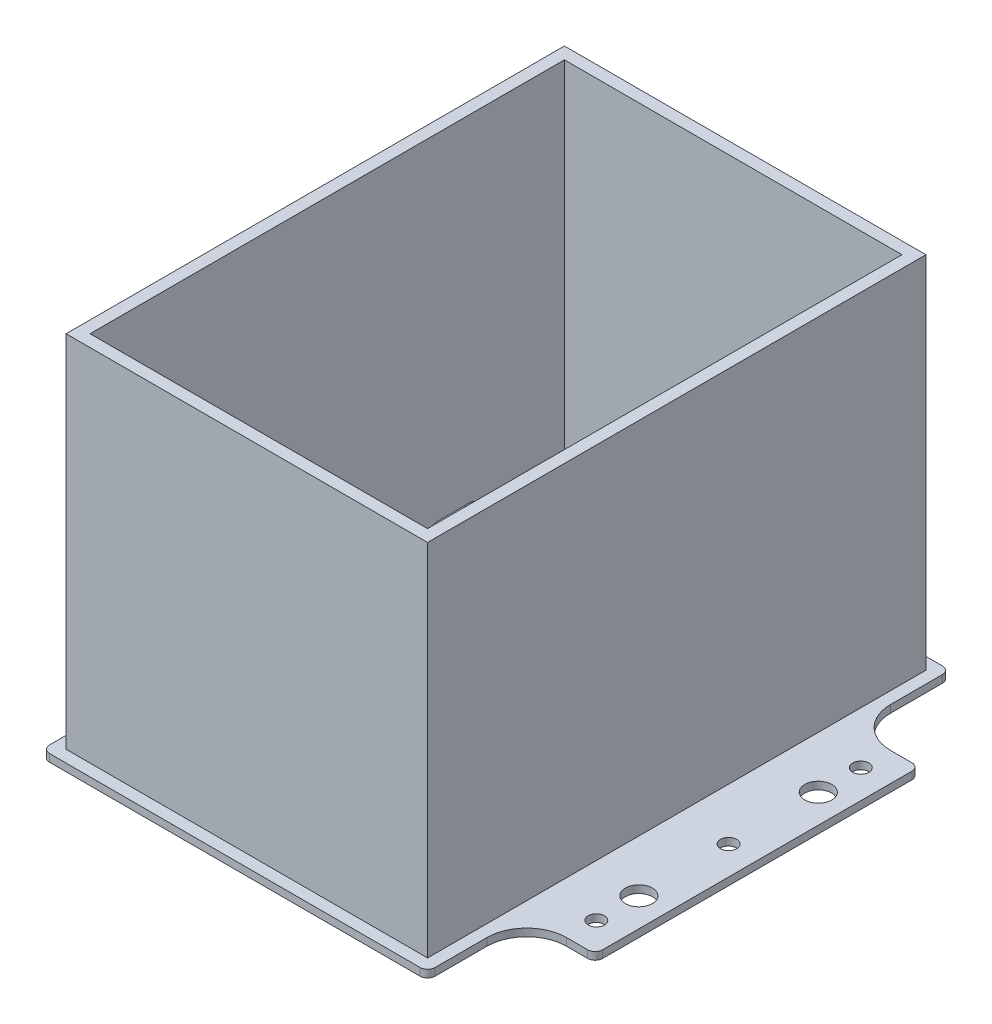
SolidWorks part; units mm, degrees
ref_plane "Front Plane" through (0, 0, 0) normal (0, 0, 1) x (1, 0, 0)
ref_plane "Top Plane" through (0, 0, 0) normal (0, 1, 0) x (1, 0, 0)
ref_plane "Right Plane" through (0, 0, 0) normal (1, 0, 0) x (0, 0, -1)
sketch "Sketch1" plane through (0, 0, 0) normal (0, 1, 0) x (1, 0, 0)
  line L0 (0, 22.5679) -> (0, 88.0491)
  line L1 (1.5748, 89.6239) -> (6.0579, 89.6239)
  line L2 (14.4907, 98.0567) -> (14.4907, 109.0422)
  line L3 (16.0655, 110.617) -> (94.5515, 110.617)
  line L4 (96.1263, 109.0422) -> (96.1263, 98.0567)
  line L5 (104.5591, 89.6239) -> (109.0422, 89.6239)
  line L6 (110.617, 88.0491) -> (110.617, 22.5679)
  line L7 (109.0422, 20.9931) -> (104.5591, 20.9931)
  line L8 (96.1263, 12.5603) -> (96.1263, 1.5748)
  line L9 (94.5515, 0) -> (16.0655, 0)
  line L10 (14.4907, 1.5748) -> (14.4907, 12.5603)
  line L11 (6.0579, 20.9931) -> (1.5748, 20.9931)
  line L12 (6.0579, 98.0567) -> (6.0579, 12.5603) construction
  line L13 (104.5591, 98.0567) -> (104.5591, 12.5603) construction
  line L14 (55.3085, 110.617) -> (55.3085, 0) construction
  line L15 (0, 55.3085) -> (110.617, 55.3085) construction
  arc A0 (6.0579, 20.9931) -> (14.4907, 12.5603) centre (6.0579, 12.5603) cw
  arc A1 (104.5591, 20.9931) -> (96.1263, 12.5603) centre (104.5591, 12.5603) ccw
  arc A2 (96.1263, 98.0567) -> (104.5591, 89.6239) centre (104.5591, 98.0567) ccw
  arc A3 (6.0579, 89.6239) -> (14.4907, 98.0567) centre (6.0579, 98.0567) ccw
  arc A4 (1.5748, 89.6239) -> (0, 88.0491) centre (1.5748, 88.0491) ccw
  arc A5 (0, 22.5679) -> (1.5748, 20.9931) centre (1.5748, 22.5679) ccw
  arc A6 (16.0655, 0) -> (14.4907, 1.5748) centre (16.0655, 1.5748) cw
  arc A7 (94.5515, 0) -> (96.1263, 1.5748) centre (94.5515, 1.5748) ccw
  arc A8 (110.617, 22.5679) -> (109.0422, 20.9931) centre (109.0422, 22.5679) cw
  arc A9 (109.0422, 89.6239) -> (110.617, 88.0491) centre (109.0422, 88.0491) cw
  arc A10 (96.1263, 109.0422) -> (94.5515, 110.617) centre (94.5515, 109.0422) ccw
  arc A11 (16.0655, 110.617) -> (14.4907, 109.0422) centre (16.0655, 109.0422) ccw
  circle A12 centre (6.0579, 83.312) radius 1.7145
  circle A13 centre (6.0579, 27.305) radius 1.7145
  circle A14 centre (6.0579, 55.3085) radius 1.7145
  circle A15 centre (104.5591, 83.312) radius 1.7145
  circle A16 centre (104.5591, 55.3085) radius 1.7145
  circle A17 centre (104.5591, 27.305) radius 1.7145
  circle A18 centre (6.0579, 74.3077) radius 2.8575
  circle A19 centre (104.5591, 74.3077) radius 2.8575
  circle A20 centre (104.5591, 36.3093) radius 2.8575
  circle A21 centre (6.0579, 36.3093) radius 2.8575
  point P24 (0, 89.6239)
  point P27 (0, 20.9931)
  point P30 (14.4907, 0)
  point P33 (96.1263, 0)
  point P67 (0, 0)
  dimension "D5" = 8.4328
  dimension "D6" = 1.5748
  dimension "D7" = 3.429
  dimension "D8" = 3.429
  dimension "D9" = 3.429
  dimension "D10" = 3.429
  dimension "D11" = 3.429
  dimension "D12" = 3.429
  dimension "D14" = 5.715
  dimension "D15" = 5.715
  dimension "D16" = 5.715
  dimension "D17" = 5.715
  dimension "D1" = 81.6356
  dimension "D2" = 68.6308
  dimension "D3" = 110.617
  dimension "D4" = 110.617
  dimension "D13" = 56.007
  dimension "D18" = 37.9984
extrude "Base" add sketch "Sketch1" along normal blind 1.6002
sketch "Wall Base" plane through (0, 1.6002, 0) normal (0, 1, 0) x (1, 0, 0)
  line L12 (94.5515, 110.617) -> (16.0655, 110.617) construction
  line L14 (96.1263, 1.5748) -> (96.1263, 12.5603) construction
  line L15 (16.0655, 0) -> (94.5515, 0) construction
  line L49 (14.4907, 109.0422) -> (14.4907, 98.0567) construction
  line L50 (17.0307, 2.54) -> (93.5863, 2.54)
  line L51 (17.0307, 2.54) -> (17.0307, 108.077)
  line L52 (17.0307, 108.077) -> (93.5863, 108.077)
  line L53 (93.5863, 2.54) -> (93.5863, 108.077)
  line L54 (19.5707, 5.08) -> (19.5707, 105.537)
  line L55 (19.5707, 105.537) -> (91.0463, 105.537)
  line L56 (91.0463, 5.08) -> (91.0463, 105.537)
  line L57 (19.5707, 5.08) -> (91.0463, 5.08)
  dimension "D1" = 2.54
  dimension "D2" = 2.54
  dimension "D3" = 2.54
  dimension "D4" = 2.54
  dimension "D5" = 2.54
sketch "Sketch3" plane through (0, 1.6002, 0) normal (0, 1, 0) x (1, 0, 0)
  line L0 (0, 55.3085) -> (110.617, 55.3085) construction
  line L5 (0, 88.0491) -> (0, 22.5679) construction
  line L6 (110.617, 22.5679) -> (110.617, 88.0491) construction
  line L7 (55.3085, 110.617) -> (55.3085, 0) construction
  line L8 (94.5515, 110.617) -> (16.0655, 110.617) construction
  line L9 (16.0655, 0) -> (94.5515, 0) construction
  line L11 (83.3719, 20.6808) -> (89.7219, 20.6808)
  line L12 (83.3719, 20.6808) -> (83.3719, 89.9362)
  line L13 (83.3719, 89.9362) -> (89.7219, 89.9362)
  line L14 (89.7219, 20.6808) -> (89.7219, 89.9362)
  point P22 (83.3719, 55.3085)
  dimension "D1" = 6.35
extrude "Breadboard Slice" cut sketch "Sketch3" against normal blind 0.8001
sketch "RPi Holes + Sizing" plane through (0, 1.6002, 0) normal (0, 1, 0) x (1, 0, 0)
  line L1 (21.6255, 8.4583) -> (80.0255, 8.4583) construction
  line L2 (21.6255, 8.4583) -> (21.6255, 97.0583) construction
  line L3 (21.6255, 97.0583) -> (24.0255, 97.0583) construction
  line L4 (80.0255, 8.4583) -> (80.0255, 12.0583) construction
  line L5 (80.0255, 97.0583) -> (24.0255, 97.0583) construction
  line L6 (80.0255, 97.0583) -> (80.0255, 12.0583) construction
  line L7 (80.0255, 12.0583) -> (24.0255, 12.0583) construction
  line L8 (24.0255, 97.0583) -> (24.0255, 12.0583) construction
  circle A0 centre (27.5255, 93.5583) radius 1.35
  circle A1 centre (76.5255, 93.5583) radius 1.35
  circle A2 centre (27.5255, 35.5583) radius 1.35
  circle A3 centre (76.5255, 35.5583) radius 1.35
  point P11 (76.2301, 93.674)
  point P14 (27.3717, 57.5513)
  point P17 (76.2301, 57.5513)
  point P18 (0, 0)
  point P19 (0, 0)
  point P20 (0, 0)
  point P21 (0, 0)
  point P22 (75.6512, 93.5583)
  dimension "D1" = 2.7
  dimension "D2" = 58
  dimension "D3" = 85
  dimension "D4" = 56
  dimension "D5" = 3.5
  dimension "D6" = 3.5
  dimension "D7" = 3.5
extrude "RPi Holes" cut sketch "RPi Holes + Sizing" against normal through all
extrude "Wall" add sketch "Wall Base" along normal blind 76.2
sketch "Sketch6" plane through (17.0307, 0, 0) normal (-1, 0, 0) x (0, 0, 1)
  line L1 (-85.6337, 3.1002) -> (-78.7833, 3.1002)
  line L2 (-87.2085, 4.675) -> (-87.2085, 5.0254)
  line L3 (-85.6337, 6.6002) -> (-78.7833, 6.6002)
  line L4 (-77.2085, 4.675) -> (-77.2085, 5.0254)
  line L6 (-108.077, 1.6002) -> (-2.54, 1.6002) construction
  arc A0 (-77.2085, 5.0254) -> (-78.7833, 6.6002) centre (-78.7833, 5.0254) ccw
  arc A1 (-78.7833, 3.1002) -> (-77.2085, 4.675) centre (-78.7833, 4.675) ccw
  arc A2 (-87.2085, 4.675) -> (-85.6337, 3.1002) centre (-85.6337, 4.675) ccw
  arc A3 (-87.2085, 5.0254) -> (-85.6337, 6.6002) centre (-85.6337, 5.0254) cw
  point P4 (0, 0)
  point P10 (-77.2085, 6.6002)
  point P15 (-87.2085, 3.1002)
  point P18 (-87.2085, 6.6002)
  point P19 (0, 0)
  dimension "D4" = 1.5748
  dimension "D1" = 3.5
  dimension "D2" = 1.5
  dimension "D3" = 10
extrude "USBC" cut sketch "Sketch6" against normal up to surface (2.54 mm away) up to face at (19.5707, 39.7002, -55.3085)
